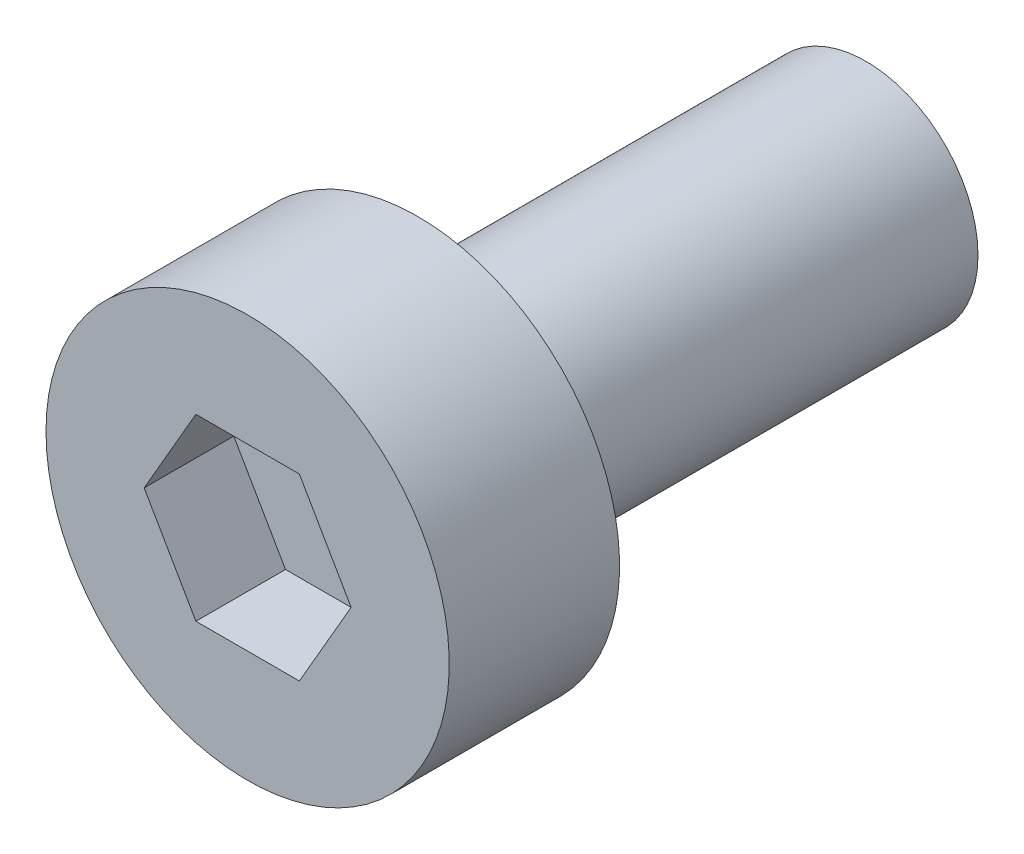
SolidWorks part; units mm, degrees
ref_plane "Plan de face" through (0, 0, 0) normal (0, 0, 1) x (1, 0, 0)
ref_plane "Plan de dessus" through (0, 0, 0) normal (0, 1, 0) x (1, 0, 0)
ref_plane "Plan de droite" through (0, 0, 0) normal (1, 0, 0) x (0, 0, -1)
sketch "Esquisse1" plane through (0, 0, 0) normal (0, 0, 1) x (1, 0, 0)
  circle A0 centre (0, 0) radius 1.25
  dimension "D1" = 2.5
extrude "Boss.-Extru.1" add sketch "Esquisse1" along normal blind 5
sketch "Esquisse2" plane through (0, 0, 5) normal (0, 0, 1) x (1, 0, 0)
  circle A0 centre (0, 0) radius 2.25
  dimension "D1" = 4.5
extrude "Boss.-Extru.2" add sketch "Esquisse2" along normal blind 1.9
sketch "Esquisse3" plane through (0, 0, 6.9) normal (0, 0, 1) x (1, 0, 0)
  line L1 (1.1547, 0) -> (0.5774, 1)
  line L2 (0.5774, 1) -> (-0.5774, 1)
  line L3 (-0.5774, 1) -> (-1.1547, 0)
  line L4 (-1.1547, 0) -> (-0.5774, -1)
  line L5 (-0.5774, -1) -> (0.5774, -1)
  line L6 (0.5774, -1) -> (1.1547, 0)
  circle A0 centre (0, 0) radius 1 construction
  dimension "D1" = 2
extrude "Enlèv. mat.-Extru.1" cut sketch "Esquisse3" against normal blind 1
